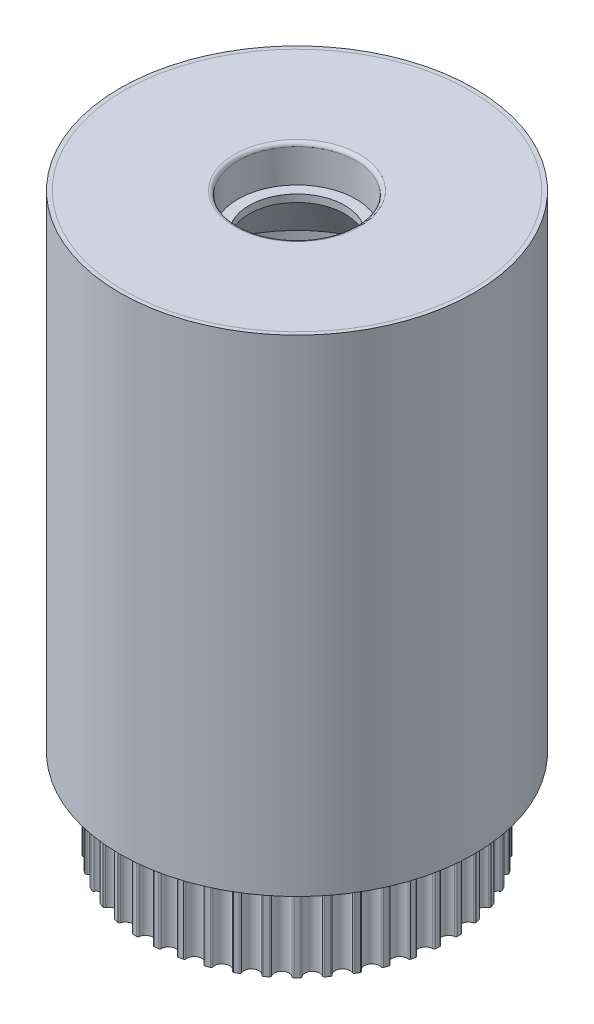
SolidWorks part; units mm, degrees
ref_plane "Front Plane" through (0, 0, 0) normal (0, 0, 1) x (1, 0, 0)
ref_plane "Top Plane" through (0, 0, 0) normal (0, 1, 0) x (1, 0, 0)
ref_plane "Right Plane" through (0, 0, 0) normal (1, 0, 0) x (0, 0, -1)
sketch "Sketch1" plane through (0, 0, 0) normal (0, 0, 1) x (1, 0, 0)
  line L0 (0, 126.6549) -> (0, -44.1569) construction
  line L1 (8, 78) -> (23.5, 78)
  line L2 (23.5, 78) -> (23.5, 12)
  line L3 (23.5, 12) -> (20.625, 12)
  line L4 (20.625, 12) -> (20.625, 0)
  line L5 (20.625, 0) -> (8, 0)
  line L6 (8, 78) -> (8, 73)
  line L7 (6.5, 73) -> (6.5, 72)
  line L8 (6.5, 72) -> (10.5, 72)
  line L9 (6.5, 73) -> (8, 73)
  line L10 (10.5, 72) -> (16, 62)
  line L11 (16, 62) -> (16, 15)
  line L12 (16, 15) -> (10, 10)
  line L13 (8, 0) -> (8, 5)
  line L14 (8, 5) -> (6.5, 5)
  line L15 (6.5, 5) -> (6.5, 10)
  line L16 (6.5, 10) -> (10, 10)
  point P24 (8, 75.5)
  dimension "D1" = 78
  dimension "D2" = 8
  dimension "D3" = 8
  dimension "D4" = 23.5
  dimension "D5" = 6.5
  dimension "D6" = 6.5
  dimension "D7" = 1
  dimension "D8" = 5
  dimension "D9" = 5
  dimension "D10" = 5
  dimension "D11" = 12
  dimension "D12" = 20.625
  dimension "D13" = 47
  dimension "D14" = 10
  dimension "D15" = 16
  dimension "D16" = 4
  dimension "D17" = 10
revolve "Revolve1" add sketch "Sketch1" angle 360 about L0
fillet "Fillet1" radius 0.5 2 edges at (0, 0, 8) (0, 78, 8)
sketch "Sketch3" plane through (0, 0, 0) normal (0, -1, 0) x (1, 0, 0)
  line L0 (0, 0) -> (0, 20.575) construction
  circle A0 centre (0, 20.575) radius 1
  circle A1 centre (0, 0) radius 20.625 construction
  circle A2 centre (2.9281, 20.3656) radius 1
  circle A3 centre (5.7966, 19.7416) radius 1
  circle A4 centre (8.5472, 18.7157) radius 1
  circle A5 centre (11.1237, 17.3088) radius 1
  circle A6 centre (13.4738, 15.5495) radius 1
  circle A7 centre (15.5495, 13.4738) radius 1
  circle A8 centre (17.3088, 11.1237) radius 1
  circle A9 centre (18.7157, 8.5472) radius 1
  circle A10 centre (19.7416, 5.7966) radius 1
  circle A11 centre (20.3656, 2.9281) radius 1
  circle A12 centre (20.575, 0) radius 1
  circle A13 centre (20.3656, -2.9281) radius 1
  circle A14 centre (19.7416, -5.7966) radius 1
  circle A15 centre (18.7157, -8.5472) radius 1
  circle A16 centre (17.3088, -11.1237) radius 1
  circle A17 centre (15.5495, -13.4738) radius 1
  circle A18 centre (13.4738, -15.5495) radius 1
  circle A19 centre (11.1237, -17.3088) radius 1
  circle A20 centre (8.5472, -18.7157) radius 1
  circle A21 centre (5.7966, -19.7416) radius 1
  circle A22 centre (2.9281, -20.3656) radius 1
  circle A23 centre (0, -20.575) radius 1
  circle A24 centre (-2.9281, -20.3656) radius 1
  circle A25 centre (-5.7966, -19.7416) radius 1
  circle A26 centre (-8.5472, -18.7157) radius 1
  circle A27 centre (-11.1237, -17.3088) radius 1
  circle A28 centre (-13.4738, -15.5495) radius 1
  circle A29 centre (-15.5495, -13.4738) radius 1
  circle A30 centre (-17.3088, -11.1237) radius 1
  circle A31 centre (-18.7157, -8.5472) radius 1
  circle A32 centre (-19.7416, -5.7966) radius 1
  circle A33 centre (-20.3656, -2.9281) radius 1
  circle A34 centre (-20.575, 0) radius 1
  circle A35 centre (-20.3656, 2.9281) radius 1
  circle A36 centre (-19.7416, 5.7966) radius 1
  circle A37 centre (-18.7157, 8.5472) radius 1
  circle A38 centre (-17.3088, 11.1237) radius 1
  circle A39 centre (-15.5495, 13.4738) radius 1
  circle A40 centre (-13.4738, 15.5495) radius 1
  circle A42 centre (0, 0) radius 20.625 construction
  circle A43 centre (-11.1237, 17.3088) radius 1
  circle A44 centre (-8.5472, 18.7157) radius 1
  circle A45 centre (-5.7966, 19.7416) radius 1
  circle A46 centre (-2.9281, 20.3656) radius 1
  point P4 (0, 20.625)
  point P8 (0.9997, 20.6008)
  point P9 (1.9423, 20.5333)
  point P90 (0, 0)
  point P92 (0, 0)
  dimension "D1" = 2
  dimension "D2" = 0.05
  dimension "D3" = 44
extrude "Cut-Extrude1" cut sketch "Sketch3" against normal up to surface (12 mm away) up to face at (0, 12, 23.5)
fillet "Fillet2" radius 0.2 88 edges at (-19.4846, 6, -6.7631) (-20.0479, 6, -4.8447) (-18.3238, 6, -9.4672) (-19.1544, 6, -7.6485) (-16.79, 6, -11.9786) (-17.8709, 6, -10.2966) (-14.9144, 6, -14.2461) (-16.2237, 6, -12.7351) (-12.7351, 6, -16.2237) (-14.2461, 6, -14.9144) (-10.2966, 6, -17.8709) (-11.9786, 6, -16.79) (-7.6485, 6, -19.1544) (-9.4672, 6, -18.3238) (-4.8447, 6, -20.0479) (-6.7631, 6, -19.4846) (-1.9423, 6, -20.5333) (-3.9213, 6, -20.2488) (0.9997, 6, -20.6008) (-0.9997, 6, -20.6008) (3.9213, 6, -20.2488) (1.9423, 6, -20.5333) (6.7631, 6, -19.4846) (4.8447, 6, -20.0479) (9.4672, 6, -18.3238) (7.6485, 6, -19.1544) (11.9786, 6, -16.79) (10.2966, 6, -17.8709) (14.2461, 6, -14.9144) (12.7351, 6, -16.2237) (16.2237, 6, -12.7351) (14.9144, 6, -14.2461) (17.8709, 6, -10.2966) (16.79, 6, -11.9786) (19.1544, 6, -7.6485) (18.3238, 6, -9.4672) (20.0479, 6, -4.8447) (19.4846, 6, -6.7631) (20.5333, 6, -1.9423) (20.2488, 6, -3.9213) (20.6008, 6, 0.9997) (20.6008, 6, -0.9997) (20.2488, 6, 3.9213) (20.5333, 6, 1.9423) (19.4846, 6, 6.7631) (20.0479, 6, 4.8447) (18.3238, 6, 9.4672) (19.1544, 6, 7.6485) (16.79, 6, 11.9786) (17.8709, 6, 10.2966) (14.9144, 6, 14.2461) (16.2237, 6, 12.7351) (12.7351, 6, 16.2237) (14.2461, 6, 14.9144) (10.2966, 6, 17.8709) (11.9786, 6, 16.79) (7.6485, 6, 19.1544) (9.4672, 6, 18.3238) (4.8447, 6, 20.0479) (6.7631, 6, 19.4846) (1.9423, 6, 20.5333) (3.9213, 6, 20.2488) (-0.9997, 6, 20.6008) (0.9997, 6, 20.6008) (-14.2461, 6, 14.9144) (-12.7351, 6, 16.2237) (-16.2237, 6, 12.7351) (-14.9144, 6, 14.2461) (-17.8709, 6, 10.2966) (-16.79, 6, 11.9786) (-19.1544, 6, 7.6485) (-18.3238, 6, 9.4672) (-20.0479, 6, 4.8447) (-19.4846, 6, 6.7631) (-20.5333, 6, 1.9423) (-20.2488, 6, 3.9213) (-20.6008, 6, -0.9997) (-20.6008, 6, 0.9997) (-20.2488, 6, -3.9213) (-20.5333, 6, -1.9423) (-11.9786, 6, 16.79) (-10.2966, 6, 17.8709) (-3.9213, 6, 20.2488) (-1.9423, 6, 20.5333) (-6.7631, 6, 19.4846) (-4.8447, 6, 20.0479) (-9.4672, 6, 18.3238) (-7.6485, 6, 19.1544)
sketch "Sketch4" plane through (0, 78, 0) normal (0, 1, 0) x (1, 0, 0)
  circle A0 centre (0, 0) radius 23.5
  circle A1 centre (0, 0) radius 24.05
  circle A2 centre (0, 0) radius 23.5 construction
  dimension "D1" = 0.55
extrude "Boss-Extrude1" add sketch "Sketch4" against normal up to surface (66 mm away) separate body up to face at (0, 12, 23.5)
